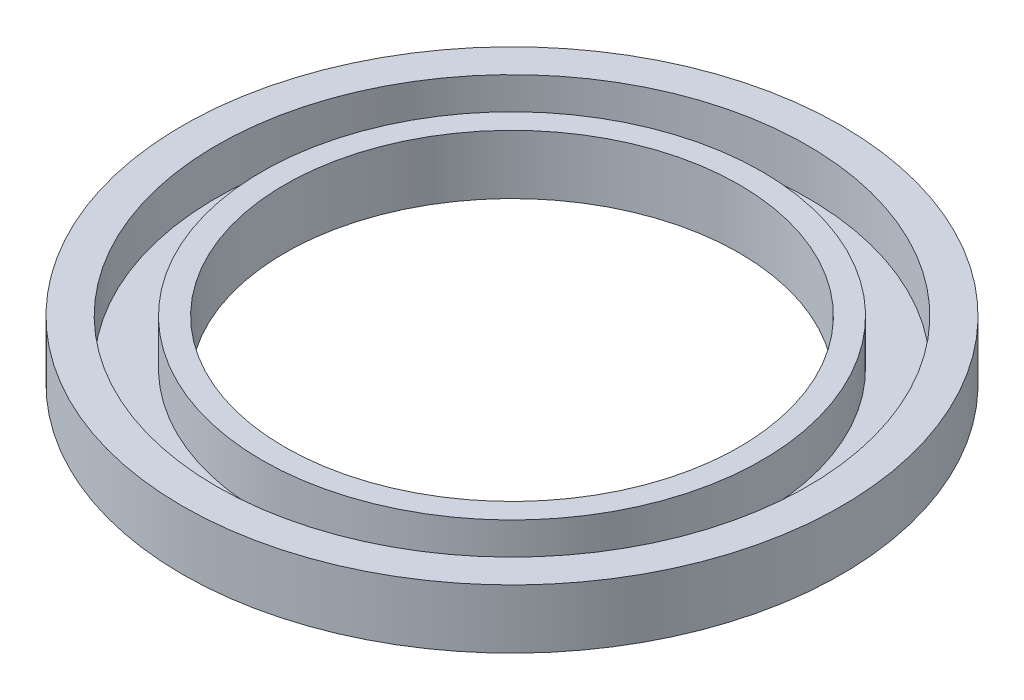
SolidWorks part; units mm, degrees
ref_plane "前视基准面" through (0, 0, 0) normal (0, 0, 1) x (1, 0, 0)
ref_plane "上视基准面" through (0, 0, 0) normal (0, 1, 0) x (1, 0, 0)
ref_plane "右视基准面" through (0, 0, 0) normal (1, 0, 0) x (0, 0, -1)
other "Configuration Table"
sketch "草图1" plane through (0, 0, 0) normal (0, 1, 0) x (1, 0, 0)
  circle A0 centre (0, 0) radius 50
  circle A1 centre (0, 0) radius 72.5
  dimension "D1" = 145
  dimension "D2" = 100
extrude "凸台-拉伸1" add sketch "草图1" along normal blind 13
sketch "草图2" plane through (0, 13, 0) normal (0, 1, 0) x (1, 0, 0)
  circle A0 centre (0, 0) radius 65
  circle A1 centre (0, 0) radius 55
  dimension "D1" = 130
  dimension "D2" = 110
extrude "切除-拉伸1" cut sketch "草图2" against normal blind 10
ref_plane "基准面1" through (0, 8, 0) normal (0, 1, 0) x (1, 0, 0)
equation "\"62。5\"=63.4933"
